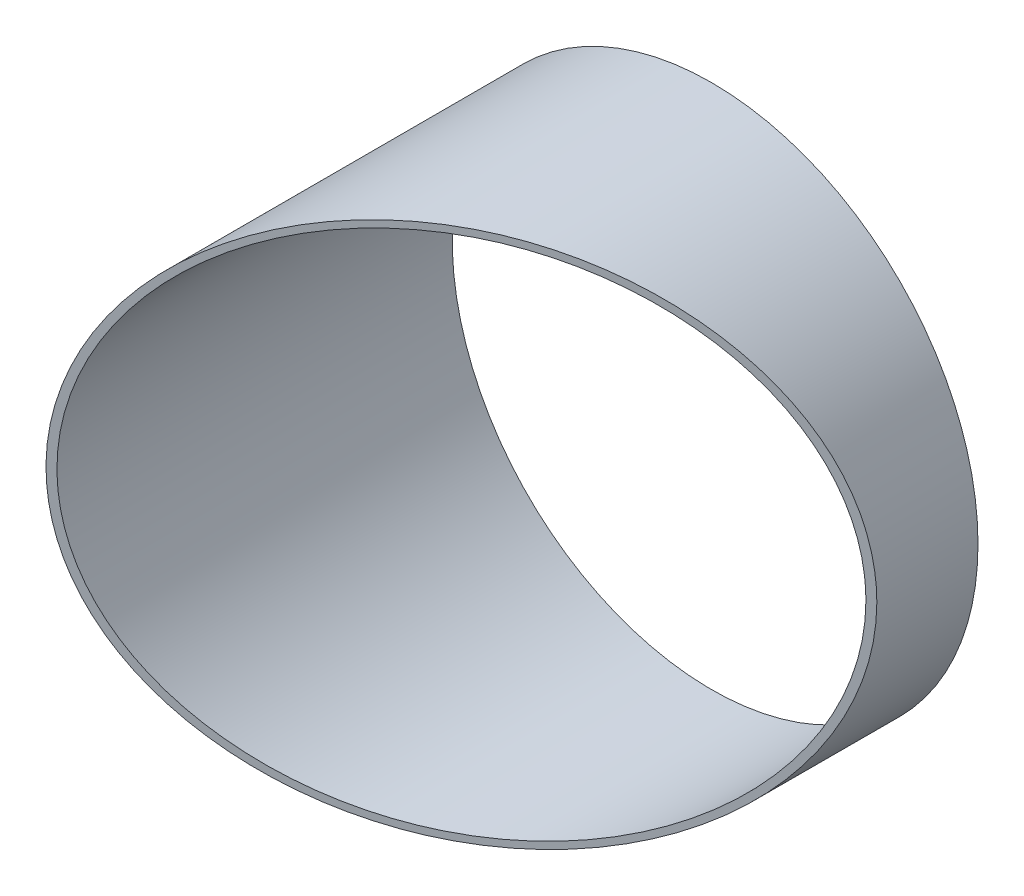
SolidWorks part; units mm, degrees
ref_plane "Front Plane" through (0, 0, 0) normal (0, 0, 1) x (1, 0, 0)
ref_plane "Top Plane" through (0, 0, 0) normal (0, 1, 0) x (1, 0, 0)
ref_plane "Right Plane" through (0, 0, 0) normal (1, 0, 0) x (0, 0, -1)
sketch "Sketch1" plane through (0, 0, 0) normal (0, 0, 1) x (1, 0, 0)
  circle A0 centre (0, 0) radius 38
  circle A1 centre (0, 0) radius 37
  dimension "D1" = 76
  dimension "D2" = 1
extrude "Boss-Extrude1" add sketch "Sketch1" along normal blind 100
sketch "Sketch2" plane through (0, 0, 0) normal (0, 1, 0) x (1, 0, 0)
  line L0 (0, 0) -> (0, -55.6916) construction
  line L1 (-38, -56.9528) -> (-53.9518, -56.9528)
  line L2 (-53.9518, -56.9528) -> (-53.9518, -117.9833)
  line L6 (38, -14.4304) -> (-38, -56.9528)
  line L7 (-53.9518, -117.9833) -> (80.7382, -117.9833)
  line L8 (80.7382, -117.9833) -> (80.7382, -14.4304)
  line L9 (80.7382, -14.4304) -> (38, -14.4304)
  point P8 (-318.7361, 505.0876)
  point P9 (-318.7361, 449.396)
extrude "Cut-Extrude1" cut sketch "Sketch2" against normal through all and the other way through all
